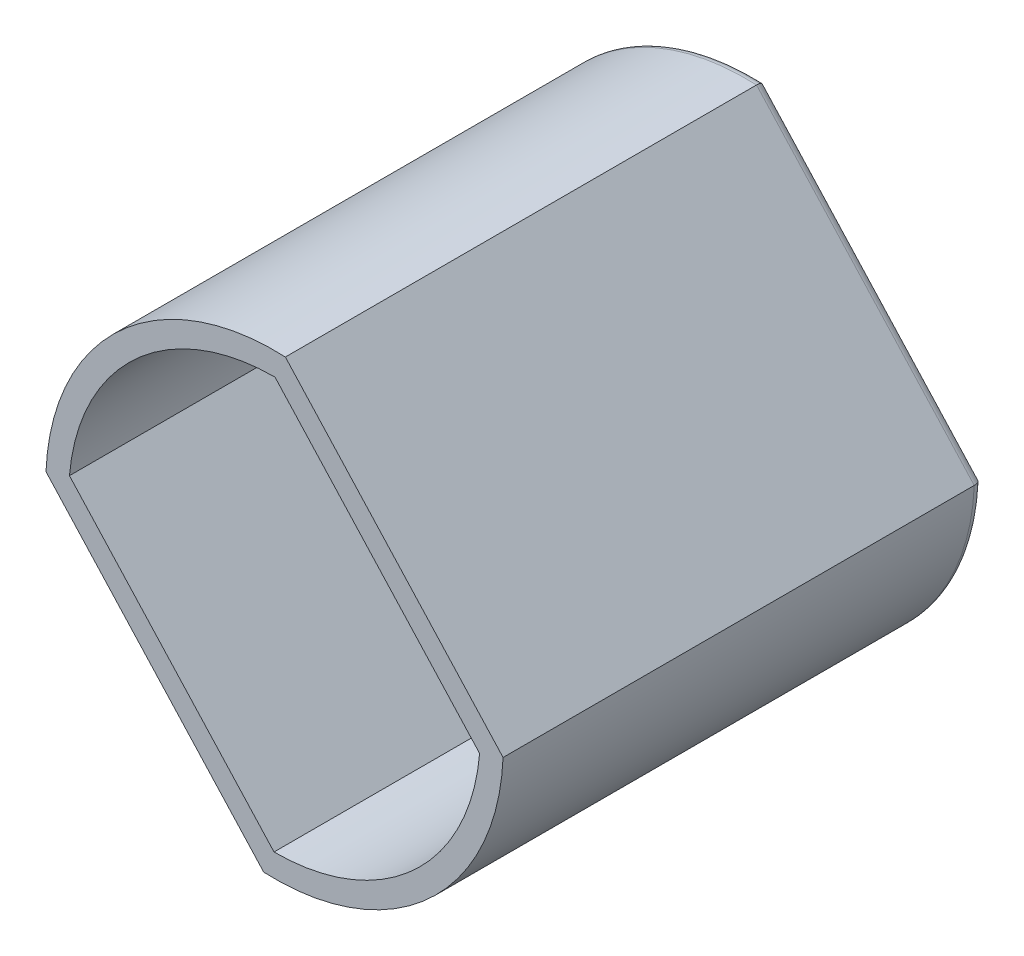
SolidWorks part; units mm, degrees
ref_plane "Front Plane" through (0, 0, 0) normal (0, 0, 1) x (1, 0, 0)
ref_plane "Top Plane" through (0, 0, 0) normal (0, 1, 0) x (1, 0, 0)
ref_plane "Right Plane" through (0, 0, 0) normal (1, 0, 0) x (0, 0, -1)
sketch "Sketch1" plane through (0, 0, 0) normal (0, 0, 1) x (1, 0, 0)
  line L0 (-9.9914, 0.4137) -> (-0.4731, -9.9888)
  line L1 (-8.9666, 0.775) -> (-0.0225, -9)
  line L2 (8.9666, -0.775) -> (0.0225, 9)
  line L3 (9.9914, -0.4137) -> (0.4731, 9.9888)
  arc A0 (-0.4731, -9.9888) -> (9.9914, -0.4137) centre (0, 0) ccw
  arc A1 (0.4731, 9.9888) -> (-9.9914, 0.4137) centre (0, 0) ccw
  arc A2 (-0.0225, -9) -> (8.9666, -0.775) centre (0, 0) ccw
  arc A3 (0.0225, 9) -> (-8.9666, 0.775) centre (0, 0) ccw
  dimension "D1" = 20
  dimension "D2" = 14.1
  dimension "D3" = 1
extrude "Boss-Extrude1" add sketch "Sketch1" along normal blind 20
sketch "Sketch2" plane through (0, 0, 0) normal (0, 0, -1) x (-1, 0, 0)
  line L2 (-0.4731, 9.9888) -> (-9.9914, -0.4137)
  line L3 (0.4731, -9.9888) -> (9.9914, 0.4137)
  line L4 (-0.4731, 9.9888) -> (-9.9914, -0.4137)
  line L5 (0.4731, -9.9888) -> (9.9914, 0.4137)
  arc A2 (9.9914, 0.4137) -> (-0.4731, 9.9888) centre (0, 0) ccw
  arc A3 (-9.9914, -0.4137) -> (0.4731, -9.9888) centre (0, 0) ccw
  arc A4 (9.9914, 0.4137) -> (-0.4731, 9.9888) centre (0, 0) ccw
  arc A5 (-9.9914, -0.4137) -> (0.4731, -9.9888) centre (0, 0) ccw
  dimension "D1" = 0
extrude "Boss-Extrude2" add sketch "Sketch2" along normal blind 1
fillet "Fillet1" radius 0.4 4 edges at (-5.2323, -4.7876, -1) (-6.7506, 7.3776, -1) (6.7506, -7.3776, -1) (5.2323, 4.7876, -1)
sketch "Sketch3" plane through (0, 0, -1) normal (0, 0, -1) x (-1, 0, 0)
  circle A0 centre (0, 0) radius 2
  dimension "D1" = 4
extrude "Boss-Extrude3" add sketch "Sketch3" along normal blind 1
sketch "Sketch4" plane through (0, 0, -2) normal (0, 0, -1) x (-1, 0, 0)
  circle A0 centre (0, 0) radius 0.75
  dimension "D1" = 1.5
extrude "Cut-Extrude1" cut sketch "Sketch4" against normal through all
